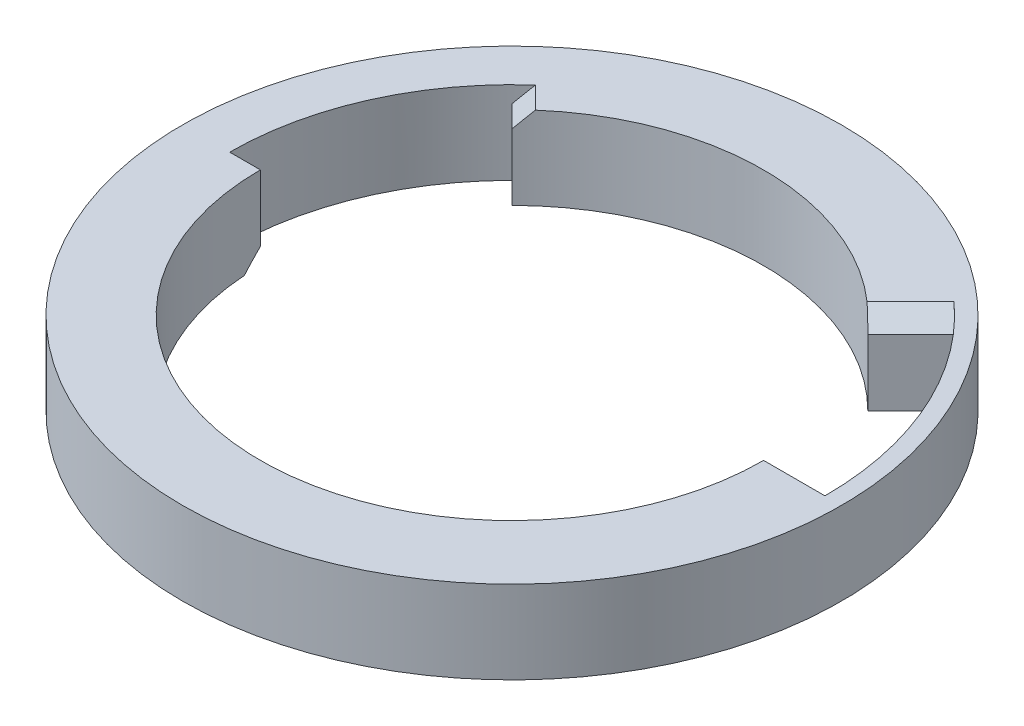
SolidWorks part; units mm, degrees
ref_plane "Front Plane" through (0, 0, 0) normal (0, 0, 1) x (1, 0, 0)
ref_plane "Top Plane" through (0, 0, 0) normal (0, 1, 0) x (1, 0, 0)
ref_plane "Right Plane" through (0, 0, 0) normal (1, 0, 0) x (0, 0, -1)
sketch "Sketch1" plane through (0, 0, 0) normal (0, 1, 0) x (1, 0, 0)
  circle A0 centre (0, 0) radius 39.75
  dimension "D1" = 79.5
extrude "Boss-Extrude1" add sketch "Sketch1" along normal blind 10
sketch "Sketch2" plane through (0, 10, 0) normal (0, 1, 0) x (1, 0, 0)
  line L0 (0, 0) -> (0, -30.35)
  line L1 (0, -30.35) -> (0, -34.05)
  line L2 (0, -34.05) -> (0, -37.75)
  line L3 (0, -37.75) -> (0, -39.75)
  line L4 (0, 0) -> (0, 30.35)
  line L5 (0, 30.35) -> (0, 34.05)
  line L6 (0, 34.05) -> (0, 37.75)
  line L7 (0, 37.75) -> (0, 39.75)
  line L8 (0, 0) -> (30.35, 0)
  line L9 (30.35, 0) -> (34.05, 0)
  line L10 (34.05, 0) -> (37.75, 0)
  line L11 (37.75, 0) -> (39.75, 0)
  line L12 (0, 0) -> (-30.35, 0)
  line L13 (-30.35, 0) -> (-34.05, 0)
  line L14 (-34.05, 0) -> (-37.75, 0)
  line L15 (-37.75, 0) -> (-39.75, 0)
  line L16 (0, 0) -> (21.4607, 21.4607)
  line L17 (21.4607, 21.4607) -> (24.077, 24.077)
  line L18 (24.077, 24.077) -> (26.6933, 26.6933)
  line L19 (26.6933, 26.6933) -> (28.1075, 28.1075)
  line L20 (0, 0) -> (-21.4607, 21.4607)
  line L21 (-21.4607, 21.4607) -> (-24.077, 24.077)
  line L22 (-24.077, 24.077) -> (-26.6933, 26.6933)
  line L23 (-26.6933, 26.6933) -> (-28.1075, 28.1075)
  circle A0 centre (0, 0) radius 37.75
  circle A1 centre (0, 0) radius 39.75 construction
  circle A2 centre (0, 0) radius 34.05
  circle A3 centre (0, 0) radius 30.35
  arc A4 (34.05, 0) -> (21.4607, 21.4607) centre (5.1596, -2.5248) ccw
  dimension "D1" = 2
  dimension "D2" = 3.7
  dimension "D3" = 3.7
extrude "Cut-Extrude4" cut sketch "Sketch2" against normal blind 10 contours L9 A4 A3 | A4 A2 L17 | A2 L10 A0 L18 | A3 L21 A2 L13
chamfer "Chamfer1" distance 2 angle 45 1 edges at (34.05, 0, 0)
chamfer "Chamfer2" distance 2 angle 45 1 edges at (-32.2, 0, 0)
chamfer "Chamfer3" distance 2 angle 45 1 edges at (24.077, 10, -24.077)
chamfer "Chamfer4" distance 2 angle 45 1 edges at (-22.7688, 10, -22.7688)
